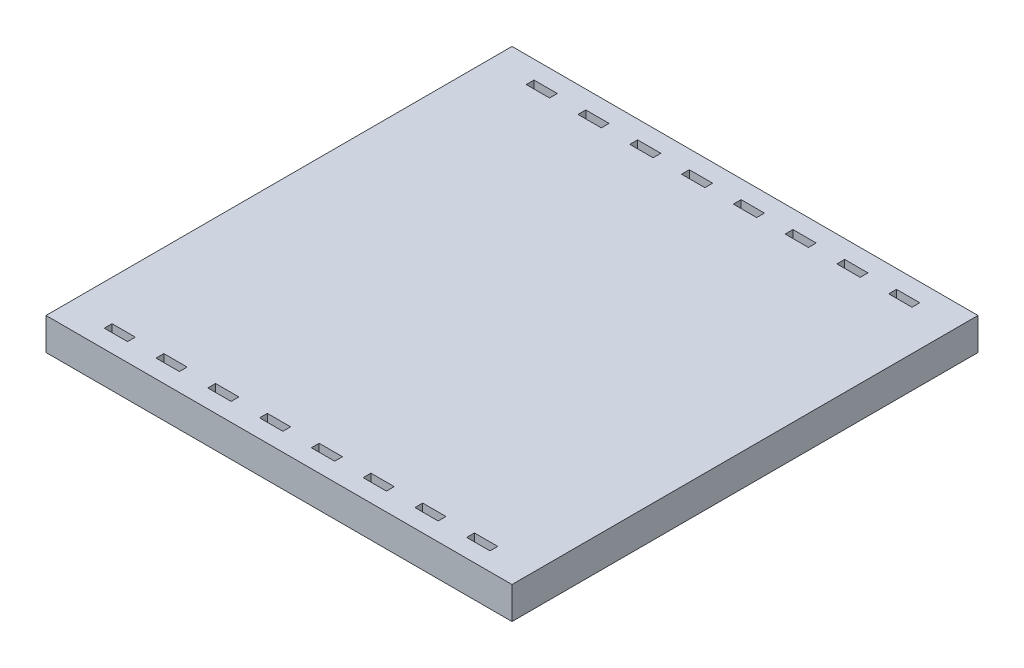
SolidWorks part; units mm, degrees
ref_plane "Front Plane" through (0, 0, 0) normal (0, 0, 1) x (1, 0, 0)
ref_plane "Top Plane" through (0, 0, 0) normal (0, 1, 0) x (1, 0, 0)
ref_plane "Right Plane" through (0, 0, 0) normal (1, 0, 0) x (0, 0, -1)
sketch "LED FOOTPRINT" plane through (0, 0, 0) normal (0, 1, 0) x (1, 0, 0)
  line L1 (0, 0) -> (80, 0) construction
  line L2 (0, 0) -> (0, -80) construction
  line L3 (0, -80) -> (80, -80) construction
  line L4 (80, 0) -> (80, -80) construction
sketch "PLUS CONTACTS" plane through (0, 0, 0) normal (0, 1, 0) x (1, 0, 0)
  line L0 (40, 0) -> (40, 5) construction
  line L1 (0, 0) -> (80, 0) construction
  line L2 (80, -39.0358) -> (85, -39.0358) construction
  line L3 (80, 0) -> (80, -80) construction
  line L4 (0, -40) -> (-5, -40) construction
  line L5 (0, 0) -> (0, -80) construction
  line L6 (40, -80) -> (40, -85) construction
  line L7 (0, -80) -> (80, -80) construction
  line L9 (-5, 5) -> (85, 5) construction
  line L10 (-5, 5) -> (-5, -85) construction
  line L11 (-5, -85) -> (85, -85) construction
  line L12 (85, 5) -> (85, -85) construction
sketch "LED OUTLINES" [suppressed] plane through (0, 0, 0) normal (0, 1, 0) x (1, 0, 0)
  line L0 (0, 0) -> (2.5, 0) construction
  line L1 (0, 0) -> (80, 0) construction
  line L2 (2.5, 0) -> (2.5, -2.5) construction
  line L3 (12.5, -2.5) -> (17.5, -2.5)
  line L4 (2.5, -2.5) -> (7.5, -2.5)
  line L5 (2.5, -2.5) -> (2.5, -7.5)
  line L6 (2.5, -7.5) -> (7.5, -7.5)
  line L7 (7.5, -2.5) -> (7.5, -7.5)
  line L8 (12.5, -2.5) -> (12.5, -7.5)
  line L9 (12.5, -7.5) -> (17.5, -7.5)
  line L10 (17.5, -2.5) -> (17.5, -7.5)
  line L11 (12.5, 0) -> (12.5, -2.5) construction
  line L12 (22.5, -2.5) -> (27.5, -2.5)
  line L13 (22.5, -2.5) -> (22.5, -7.5)
  line L14 (22.5, -7.5) -> (27.5, -7.5)
  line L15 (27.5, -2.5) -> (27.5, -7.5)
  line L16 (22.5, 0) -> (22.5, -2.5) construction
  line L17 (32.5, -2.5) -> (37.5, -2.5)
  line L18 (32.5, -2.5) -> (32.5, -7.5)
  line L19 (32.5, -7.5) -> (37.5, -7.5)
  line L20 (37.5, -2.5) -> (37.5, -7.5)
  line L21 (32.5, 0) -> (32.5, -2.5) construction
  line L22 (42.5, -2.5) -> (47.5, -2.5)
  line L23 (42.5, -2.5) -> (42.5, -7.5)
  line L24 (42.5, -7.5) -> (47.5, -7.5)
  line L25 (47.5, -2.5) -> (47.5, -7.5)
  line L26 (42.5, 0) -> (42.5, -2.5) construction
  line L27 (52.5, -2.5) -> (57.5, -2.5)
  line L28 (52.5, -2.5) -> (52.5, -7.5)
  line L29 (52.5, -7.5) -> (57.5, -7.5)
  line L30 (57.5, -2.5) -> (57.5, -7.5)
  line L31 (52.5, 0) -> (52.5, -2.5) construction
  line L32 (62.5, -2.5) -> (67.5, -2.5)
  line L33 (62.5, -2.5) -> (62.5, -7.5)
  line L34 (62.5, -7.5) -> (67.5, -7.5)
  line L35 (67.5, -2.5) -> (67.5, -7.5)
  line L36 (62.5, 0) -> (62.5, -2.5) construction
  line L37 (72.5, -2.5) -> (77.5, -2.5)
  line L38 (72.5, -2.5) -> (72.5, -7.5)
  line L39 (72.5, -7.5) -> (77.5, -7.5)
  line L40 (77.5, -2.5) -> (77.5, -7.5)
  line L41 (72.5, 0) -> (72.5, -2.5) construction
  line L42 (12.5, -12.5) -> (17.5, -12.5)
  line L43 (12.5, -12.5) -> (12.5, -17.5)
  line L44 (12.5, -17.5) -> (17.5, -17.5)
  line L45 (17.5, -12.5) -> (17.5, -17.5)
  line L46 (12.5, -10) -> (12.5, -12.5) construction
  line L47 (22.5, -12.5) -> (27.5, -12.5)
  line L48 (22.5, -12.5) -> (22.5, -17.5)
  line L49 (22.5, -17.5) -> (27.5, -17.5)
  line L50 (27.5, -12.5) -> (27.5, -17.5)
  line L51 (22.5, -10) -> (22.5, -12.5) construction
  line L52 (32.5, -12.5) -> (37.5, -12.5)
  line L53 (32.5, -12.5) -> (32.5, -17.5)
  line L54 (32.5, -17.5) -> (37.5, -17.5)
  line L55 (37.5, -12.5) -> (37.5, -17.5)
  line L56 (32.5, -10) -> (32.5, -12.5) construction
  line L57 (42.5, -12.5) -> (47.5, -12.5)
  line L58 (42.5, -12.5) -> (42.5, -17.5)
  line L59 (42.5, -17.5) -> (47.5, -17.5)
  line L60 (47.5, -12.5) -> (47.5, -17.5)
  line L61 (42.5, -10) -> (42.5, -12.5) construction
  line L62 (52.5, -12.5) -> (57.5, -12.5)
  line L63 (52.5, -12.5) -> (52.5, -17.5)
  line L64 (52.5, -17.5) -> (57.5, -17.5)
  line L65 (57.5, -12.5) -> (57.5, -17.5)
  line L66 (52.5, -10) -> (52.5, -12.5) construction
  line L67 (62.5, -12.5) -> (67.5, -12.5)
  line L68 (62.5, -12.5) -> (62.5, -17.5)
  line L69 (62.5, -17.5) -> (67.5, -17.5)
  line L70 (67.5, -12.5) -> (67.5, -17.5)
  line L71 (62.5, -10) -> (62.5, -12.5) construction
  line L72 (72.5, -12.5) -> (77.5, -12.5)
  line L73 (72.5, -12.5) -> (72.5, -17.5)
  line L74 (72.5, -17.5) -> (77.5, -17.5)
  line L75 (77.5, -12.5) -> (77.5, -17.5)
  line L76 (72.5, -10) -> (72.5, -12.5) construction
  line L77 (12.5, -22.5) -> (17.5, -22.5)
  line L78 (12.5, -22.5) -> (12.5, -27.5)
  line L79 (12.5, -27.5) -> (17.5, -27.5)
  line L80 (17.5, -22.5) -> (17.5, -27.5)
  line L81 (12.5, -20) -> (12.5, -22.5) construction
  line L82 (22.5, -22.5) -> (27.5, -22.5)
  line L83 (22.5, -22.5) -> (22.5, -27.5)
  line L84 (22.5, -27.5) -> (27.5, -27.5)
  line L85 (27.5, -22.5) -> (27.5, -27.5)
  line L86 (22.5, -20) -> (22.5, -22.5) construction
  line L87 (32.5, -22.5) -> (37.5, -22.5)
  line L88 (32.5, -22.5) -> (32.5, -27.5)
  line L89 (32.5, -27.5) -> (37.5, -27.5)
  line L90 (37.5, -22.5) -> (37.5, -27.5)
  line L91 (32.5, -20) -> (32.5, -22.5) construction
  line L92 (42.5, -22.5) -> (47.5, -22.5)
  line L93 (42.5, -22.5) -> (42.5, -27.5)
  line L94 (42.5, -27.5) -> (47.5, -27.5)
  line L95 (47.5, -22.5) -> (47.5, -27.5)
  line L96 (42.5, -20) -> (42.5, -22.5) construction
  line L97 (52.5, -22.5) -> (57.5, -22.5)
  line L98 (52.5, -22.5) -> (52.5, -27.5)
  line L99 (52.5, -27.5) -> (57.5, -27.5)
  line L100 (57.5, -22.5) -> (57.5, -27.5)
  line L101 (52.5, -20) -> (52.5, -22.5) construction
  line L102 (62.5, -22.5) -> (67.5, -22.5)
  line L103 (62.5, -22.5) -> (62.5, -27.5)
  line L104 (62.5, -27.5) -> (67.5, -27.5)
  line L105 (67.5, -22.5) -> (67.5, -27.5)
  line L106 (62.5, -20) -> (62.5, -22.5) construction
  line L107 (72.5, -22.5) -> (77.5, -22.5)
  line L108 (72.5, -22.5) -> (72.5, -27.5)
  line L109 (72.5, -27.5) -> (77.5, -27.5)
  line L110 (77.5, -22.5) -> (77.5, -27.5)
  line L111 (72.5, -20) -> (72.5, -22.5) construction
  line L112 (12.5, -32.5) -> (17.5, -32.5)
  line L113 (12.5, -32.5) -> (12.5, -37.5)
  line L114 (12.5, -37.5) -> (17.5, -37.5)
  line L115 (17.5, -32.5) -> (17.5, -37.5)
  line L116 (12.5, -30) -> (12.5, -32.5) construction
  line L117 (22.5, -32.5) -> (27.5, -32.5)
  line L118 (22.5, -32.5) -> (22.5, -37.5)
  line L119 (22.5, -37.5) -> (27.5, -37.5)
  line L120 (27.5, -32.5) -> (27.5, -37.5)
  line L121 (22.5, -30) -> (22.5, -32.5) construction
  line L122 (32.5, -32.5) -> (37.5, -32.5)
  line L123 (32.5, -32.5) -> (32.5, -37.5)
  line L124 (32.5, -37.5) -> (37.5, -37.5)
  line L125 (37.5, -32.5) -> (37.5, -37.5)
  line L126 (32.5, -30) -> (32.5, -32.5) construction
  line L127 (42.5, -32.5) -> (47.5, -32.5)
  line L128 (42.5, -32.5) -> (42.5, -37.5)
  line L129 (42.5, -37.5) -> (47.5, -37.5)
  line L130 (47.5, -32.5) -> (47.5, -37.5)
  line L131 (42.5, -30) -> (42.5, -32.5) construction
  line L132 (52.5, -32.5) -> (57.5, -32.5)
  line L133 (52.5, -32.5) -> (52.5, -37.5)
  line L134 (52.5, -37.5) -> (57.5, -37.5)
  line L135 (57.5, -32.5) -> (57.5, -37.5)
  line L136 (52.5, -30) -> (52.5, -32.5) construction
  line L137 (62.5, -32.5) -> (67.5, -32.5)
  line L138 (62.5, -32.5) -> (62.5, -37.5)
  line L139 (62.5, -37.5) -> (67.5, -37.5)
  line L140 (67.5, -32.5) -> (67.5, -37.5)
  line L141 (62.5, -30) -> (62.5, -32.5) construction
  line L142 (72.5, -32.5) -> (77.5, -32.5)
  line L143 (72.5, -32.5) -> (72.5, -37.5)
  line L144 (72.5, -37.5) -> (77.5, -37.5)
  line L145 (77.5, -32.5) -> (77.5, -37.5)
  line L146 (72.5, -30) -> (72.5, -32.5) construction
  line L147 (12.5, -42.5) -> (17.5, -42.5)
  line L148 (12.5, -42.5) -> (12.5, -47.5)
  line L149 (12.5, -47.5) -> (17.5, -47.5)
  line L150 (17.5, -42.5) -> (17.5, -47.5)
  line L151 (12.5, -40) -> (12.5, -42.5) construction
  line L152 (22.5, -42.5) -> (27.5, -42.5)
  line L153 (22.5, -42.5) -> (22.5, -47.5)
  line L154 (22.5, -47.5) -> (27.5, -47.5)
  line L155 (27.5, -42.5) -> (27.5, -47.5)
  line L156 (22.5, -40) -> (22.5, -42.5) construction
  line L157 (32.5, -42.5) -> (37.5, -42.5)
  line L158 (32.5, -42.5) -> (32.5, -47.5)
  line L159 (32.5, -47.5) -> (37.5, -47.5)
  line L160 (37.5, -42.5) -> (37.5, -47.5)
  line L161 (32.5, -40) -> (32.5, -42.5) construction
  line L162 (42.5, -42.5) -> (47.5, -42.5)
  line L163 (42.5, -42.5) -> (42.5, -47.5)
  line L164 (42.5, -47.5) -> (47.5, -47.5)
  line L165 (47.5, -42.5) -> (47.5, -47.5)
  line L166 (42.5, -40) -> (42.5, -42.5) construction
  line L167 (52.5, -42.5) -> (57.5, -42.5)
  line L168 (52.5, -42.5) -> (52.5, -47.5)
  line L169 (52.5, -47.5) -> (57.5, -47.5)
  line L170 (57.5, -42.5) -> (57.5, -47.5)
  line L171 (52.5, -40) -> (52.5, -42.5) construction
  line L172 (62.5, -42.5) -> (67.5, -42.5)
  line L173 (62.5, -42.5) -> (62.5, -47.5)
  line L174 (62.5, -47.5) -> (67.5, -47.5)
  line L175 (67.5, -42.5) -> (67.5, -47.5)
  line L176 (62.5, -40) -> (62.5, -42.5) construction
  line L177 (72.5, -42.5) -> (77.5, -42.5)
  line L178 (72.5, -42.5) -> (72.5, -47.5)
  line L179 (72.5, -47.5) -> (77.5, -47.5)
  line L180 (77.5, -42.5) -> (77.5, -47.5)
  line L181 (72.5, -40) -> (72.5, -42.5) construction
  line L182 (12.5, -52.5) -> (17.5, -52.5)
  line L183 (12.5, -52.5) -> (12.5, -57.5)
  line L184 (12.5, -57.5) -> (17.5, -57.5)
  line L185 (17.5, -52.5) -> (17.5, -57.5)
  line L186 (12.5, -50) -> (12.5, -52.5) construction
  line L187 (22.5, -52.5) -> (27.5, -52.5)
  line L188 (22.5, -52.5) -> (22.5, -57.5)
  line L189 (22.5, -57.5) -> (27.5, -57.5)
  line L190 (27.5, -52.5) -> (27.5, -57.5)
  line L191 (22.5, -50) -> (22.5, -52.5) construction
  line L192 (32.5, -52.5) -> (37.5, -52.5)
  line L193 (32.5, -52.5) -> (32.5, -57.5)
  line L194 (32.5, -57.5) -> (37.5, -57.5)
  line L195 (37.5, -52.5) -> (37.5, -57.5)
  line L196 (32.5, -50) -> (32.5, -52.5) construction
  line L197 (42.5, -52.5) -> (47.5, -52.5)
  line L198 (42.5, -52.5) -> (42.5, -57.5)
  line L199 (42.5, -57.5) -> (47.5, -57.5)
  line L200 (47.5, -52.5) -> (47.5, -57.5)
  line L201 (42.5, -50) -> (42.5, -52.5) construction
  line L202 (52.5, -52.5) -> (57.5, -52.5)
  line L203 (52.5, -52.5) -> (52.5, -57.5)
  line L204 (52.5, -57.5) -> (57.5, -57.5)
  line L205 (57.5, -52.5) -> (57.5, -57.5)
  line L206 (52.5, -50) -> (52.5, -52.5) construction
  line L207 (62.5, -52.5) -> (67.5, -52.5)
  line L208 (62.5, -52.5) -> (62.5, -57.5)
  line L209 (62.5, -57.5) -> (67.5, -57.5)
  line L210 (67.5, -52.5) -> (67.5, -57.5)
  line L211 (62.5, -50) -> (62.5, -52.5) construction
  line L212 (72.5, -52.5) -> (77.5, -52.5)
  line L213 (72.5, -52.5) -> (72.5, -57.5)
  line L214 (72.5, -57.5) -> (77.5, -57.5)
  line L215 (77.5, -52.5) -> (77.5, -57.5)
  line L216 (72.5, -50) -> (72.5, -52.5) construction
  line L217 (12.5, -62.5) -> (17.5, -62.5)
  line L218 (12.5, -62.5) -> (12.5, -67.5)
  line L219 (12.5, -67.5) -> (17.5, -67.5)
  line L220 (17.5, -62.5) -> (17.5, -67.5)
  line L221 (12.5, -60) -> (12.5, -62.5) construction
  line L222 (22.5, -62.5) -> (27.5, -62.5)
  line L223 (22.5, -62.5) -> (22.5, -67.5)
  line L224 (22.5, -67.5) -> (27.5, -67.5)
  line L225 (27.5, -62.5) -> (27.5, -67.5)
  line L226 (22.5, -60) -> (22.5, -62.5) construction
  line L227 (32.5, -62.5) -> (37.5, -62.5)
  line L228 (32.5, -62.5) -> (32.5, -67.5)
  line L229 (32.5, -67.5) -> (37.5, -67.5)
  line L230 (37.5, -62.5) -> (37.5, -67.5)
  line L231 (32.5, -60) -> (32.5, -62.5) construction
  line L232 (42.5, -62.5) -> (47.5, -62.5)
  line L233 (42.5, -62.5) -> (42.5, -67.5)
  line L234 (42.5, -67.5) -> (47.5, -67.5)
  line L235 (47.5, -62.5) -> (47.5, -67.5)
  line L236 (42.5, -60) -> (42.5, -62.5) construction
  line L237 (52.5, -62.5) -> (57.5, -62.5)
  line L238 (52.5, -62.5) -> (52.5, -67.5)
  line L239 (52.5, -67.5) -> (57.5, -67.5)
  line L240 (57.5, -62.5) -> (57.5, -67.5)
  line L241 (52.5, -60) -> (52.5, -62.5) construction
  line L242 (62.5, -62.5) -> (67.5, -62.5)
  line L243 (62.5, -62.5) -> (62.5, -67.5)
  line L244 (62.5, -67.5) -> (67.5, -67.5)
  line L245 (67.5, -62.5) -> (67.5, -67.5)
  line L246 (62.5, -60) -> (62.5, -62.5) construction
  line L247 (72.5, -62.5) -> (77.5, -62.5)
  line L248 (72.5, -62.5) -> (72.5, -67.5)
  line L249 (72.5, -67.5) -> (77.5, -67.5)
  line L250 (77.5, -62.5) -> (77.5, -67.5)
  line L251 (72.5, -60) -> (72.5, -62.5) construction
  line L252 (12.5, -72.5) -> (17.5, -72.5)
  line L253 (12.5, -72.5) -> (12.5, -77.5)
  line L254 (12.5, -77.5) -> (17.5, -77.5)
  line L255 (17.5, -72.5) -> (17.5, -77.5)
  line L256 (12.5, -70) -> (12.5, -72.5) construction
  line L257 (22.5, -72.5) -> (27.5, -72.5)
  line L258 (22.5, -72.5) -> (22.5, -77.5)
  line L259 (22.5, -77.5) -> (27.5, -77.5)
  line L260 (27.5, -72.5) -> (27.5, -77.5)
  line L261 (22.5, -70) -> (22.5, -72.5) construction
  line L262 (32.5, -72.5) -> (37.5, -72.5)
  line L263 (32.5, -72.5) -> (32.5, -77.5)
  line L264 (32.5, -77.5) -> (37.5, -77.5)
  line L265 (37.5, -72.5) -> (37.5, -77.5)
  line L266 (32.5, -70) -> (32.5, -72.5) construction
  line L267 (42.5, -72.5) -> (47.5, -72.5)
  line L268 (42.5, -72.5) -> (42.5, -77.5)
  line L269 (42.5, -77.5) -> (47.5, -77.5)
  line L270 (47.5, -72.5) -> (47.5, -77.5)
  line L271 (42.5, -70) -> (42.5, -72.5) construction
  line L272 (52.5, -72.5) -> (57.5, -72.5)
  line L273 (52.5, -72.5) -> (52.5, -77.5)
  line L274 (52.5, -77.5) -> (57.5, -77.5)
  line L275 (57.5, -72.5) -> (57.5, -77.5)
  line L276 (52.5, -70) -> (52.5, -72.5) construction
  line L277 (62.5, -72.5) -> (67.5, -72.5)
  line L278 (62.5, -72.5) -> (62.5, -77.5)
  line L279 (62.5, -77.5) -> (67.5, -77.5)
  line L280 (67.5, -72.5) -> (67.5, -77.5)
  line L281 (62.5, -70) -> (62.5, -72.5) construction
  line L282 (72.5, -72.5) -> (77.5, -72.5)
  line L283 (72.5, -72.5) -> (72.5, -77.5)
  line L284 (72.5, -77.5) -> (77.5, -77.5)
  line L285 (77.5, -72.5) -> (77.5, -77.5)
  line L286 (72.5, -70) -> (72.5, -72.5) construction
  line L287 (2.5, -12.5) -> (7.5, -12.5)
  line L288 (2.5, -12.5) -> (2.5, -17.5)
  line L289 (2.5, -17.5) -> (7.5, -17.5)
  line L290 (7.5, -12.5) -> (7.5, -17.5)
  line L291 (2.5, -10) -> (2.5, -12.5) construction
  line L292 (2.5, -22.5) -> (7.5, -22.5)
  line L293 (2.5, -22.5) -> (2.5, -27.5)
  line L294 (2.5, -27.5) -> (7.5, -27.5)
  line L295 (7.5, -22.5) -> (7.5, -27.5)
  line L296 (2.5, -20) -> (2.5, -22.5) construction
  line L297 (2.5, -32.5) -> (7.5, -32.5)
  line L298 (2.5, -32.5) -> (2.5, -37.5)
  line L299 (2.5, -37.5) -> (7.5, -37.5)
  line L300 (7.5, -32.5) -> (7.5, -37.5)
  line L301 (2.5, -30) -> (2.5, -32.5) construction
  line L302 (2.5, -42.5) -> (7.5, -42.5)
  line L303 (2.5, -42.5) -> (2.5, -47.5)
  line L304 (2.5, -47.5) -> (7.5, -47.5)
  line L305 (7.5, -42.5) -> (7.5, -47.5)
  line L306 (2.5, -40) -> (2.5, -42.5) construction
  line L307 (2.5, -52.5) -> (7.5, -52.5)
  line L308 (2.5, -52.5) -> (2.5, -57.5)
  line L309 (2.5, -57.5) -> (7.5, -57.5)
  line L310 (7.5, -52.5) -> (7.5, -57.5)
  line L311 (2.5, -50) -> (2.5, -52.5) construction
  line L312 (2.5, -62.5) -> (7.5, -62.5)
  line L313 (2.5, -62.5) -> (2.5, -67.5)
  line L314 (2.5, -67.5) -> (7.5, -67.5)
  line L315 (7.5, -62.5) -> (7.5, -67.5)
  line L316 (2.5, -60) -> (2.5, -62.5) construction
  line L317 (2.5, -72.5) -> (7.5, -72.5)
  line L318 (2.5, -72.5) -> (2.5, -77.5)
  line L319 (2.5, -77.5) -> (7.5, -77.5)
  line L320 (7.5, -72.5) -> (7.5, -77.5)
  line L321 (2.5, -70) -> (2.5, -72.5) construction
  dimension "D1" = 8
  dimension "D2" = 8
sketch "Outline" plane through (0, 0, 0) normal (0, 1, 0) x (1, 0, 0)
  line L0 (40, 5) -> (40, 10) construction
  line L1 (85, -39.0358) -> (90, -39.0358) construction
  line L2 (-5, -40) -> (-10, -40) construction
  line L3 (-5, 5) -> (-5, -85) construction
  line L4 (40, -85) -> (40, -90) construction
  line L6 (-10, 10) -> (90, 10)
  line L7 (-10, 10) -> (-10, -90)
  line L8 (-10, -90) -> (90, -90)
  line L9 (90, 10) -> (90, -90)
extrude "Boss-Extrude1" add sketch "Outline" along normal blind 6.2
sketch "Sketch3" plane through (0, 6.2, 0) normal (0, 1, 0) x (1, 0, 0)
  line L0 (80, -40) -> (85, -40) construction
  line L1 (80, 0) -> (80, -80) construction
  line L2 (0, -40) -> (-5, -40) construction
  line L3 (0, 0) -> (0, -80) construction
  line L4 (40, -80) -> (40, -85) construction
  line L5 (0, -80) -> (80, -80) construction
  line L6 (40, 0) -> (40, 5) construction
  line L7 (0, 0) -> (80, 0) construction
  line L9 (85, 5) -> (-5, 5)
  line L10 (85, 5) -> (85, -85)
  line L11 (85, -85) -> (-5, -85)
  line L12 (-5, 5) -> (-5, -85)
extrude "Cut-Extrude2" cut sketch "Sketch3" against normal through all flip side to cut
sketch "Sketch2" plane through (0, 6.2, 0) normal (0, 1, 0) x (1, 0, 0)
  line L0 (0, 0) -> (5, 0) construction
  line L1 (0, 0) -> (80, 0) construction
  line L2 (0, -40) -> (8.8043, -40) construction
  line L19 (5, 0) -> (10, 0) construction
  line L20 (5, 0) -> (5, 0.75) construction
  line L29 (5, -80.75) -> (1.6667, -80.75) construction
  line L30 (5, 0.75) -> (8.3333, 0.75) construction
  line L39 (5, 0.75) -> (1.6667, 0.75) construction
  line L40 (7.25, 1.5) -> (2.75, 1.5)
  line L41 (7.25, 1.5) -> (7.25, 0)
  line L42 (7.25, 0) -> (2.75, 0)
  line L43 (2.75, 1.5) -> (2.75, 0)
  line L44 (5, -80.75) -> (8.3333, -80.75) construction
  line L45 (5, -80) -> (5, -80.75) construction
  line L46 (5, -80) -> (10, -80) construction
  line L47 (0, -80) -> (5, -80) construction
  line L48 (2.75, -81.5) -> (2.75, -80)
  line L49 (7.25, -80) -> (2.75, -80)
  line L50 (7.25, -81.5) -> (7.25, -80)
  line L51 (7.25, -81.5) -> (2.75, -81.5)
  circle A0 centre (5, 0.75) radius 0.75 construction
  circle A1 centre (8.3333, 0.75) radius 0.75 construction
  circle A2 centre (1.6667, 0.75) radius 0.75 construction
  circle A6 centre (1.6667, -80.75) radius 0.75 construction
  circle A7 centre (8.3333, -80.75) radius 0.75 construction
  circle A8 centre (5, -80.75) radius 0.75 construction
extrude "Cut-Extrude1" cut sketch "Sketch2" against normal through all
pattern_linear "LPattern2" count 8 spacing 10 along (1, 0, 0) of "Cut-Extrude1"
